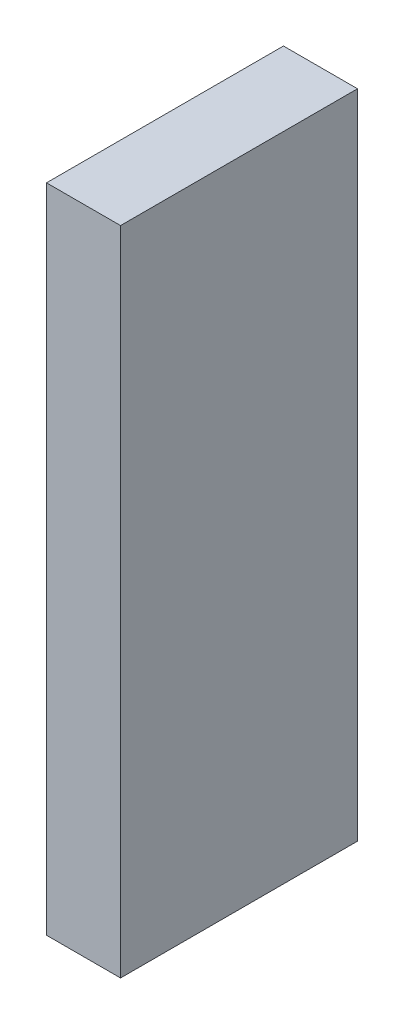
SolidWorks part; units mm, degrees
ref_plane "Front Plane" through (0, 0, 0) normal (0, 0, 1) x (1, 0, 0)
ref_plane "Top Plane" through (0, 0, 0) normal (0, 1, 0) x (1, 0, 0)
ref_plane "Right Plane" through (0, 0, 0) normal (1, 0, 0) x (0, 0, -1)
other "Configuration Table"
sketch "Sketch1" plane through (0, 0, 0) normal (0, 0, 1) x (1, 0, 0)
  line L1 (47.5, 400) -> (172.5, 400)
  line L2 (47.5, 400) -> (47.5, 1500)
  line L3 (47.5, 1500) -> (172.5, 1500)
  line L4 (172.5, 400) -> (172.5, 1500)
extrude "TOPPING_evaporator_sol_kanal_1" add sketch "Sketch1" against normal blind 400 from offset 200 separate body
